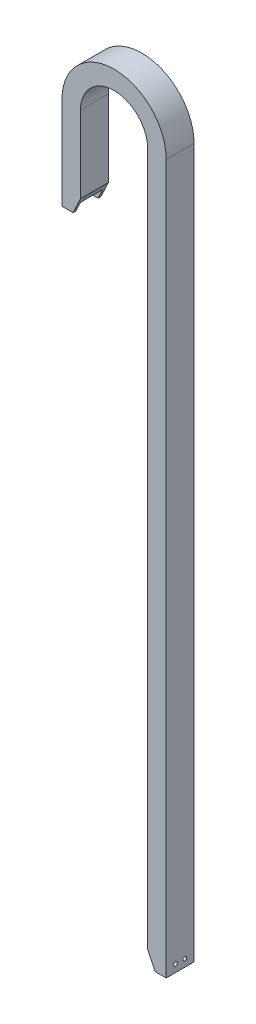
SolidWorks part; units mm, degrees
ref_plane "前视基准面" through (0, 0, 0) normal (0, 0, 1) x (1, 0, 0)
ref_plane "上视基准面" through (0, 0, 0) normal (0, 1, 0) x (1, 0, 0)
ref_plane "右视基准面" through (0, 0, 0) normal (1, 0, 0) x (0, 0, -1)
sketch "草图1" plane through (0, 0, 0) normal (0, 0, 1) x (1, 0, 0)
  line L0 (0, 0) -> (0, 100)
  line L1 (112.5, 100) -> (112.5, -665)
  line L2 (20, 0) -> (20, 100)
  line L3 (92.5, 100) -> (92.5, -665)
  line L4 (0, 0) -> (20, 0)
  line L5 (92.5, -665) -> (112.5, -665)
  arc A0 (0, 100) -> (112.5, 100) centre (56.25, 100) cw
  arc A1 (20, 100) -> (92.5, 100) centre (56.25, 100) cw
  dimension "D1" = 100
  dimension "D3" = 112.5
  dimension "D4" = 765
  dimension "D2" = 20
extrude "凸台-拉伸1" add sketch "草图1" along normal mid plane 30
shell "抽壳1" thickness 3
sketch "草图3" plane through (0, 0, 15) normal (0, 0, 1) x (1, 0, 0)
  line L0 (12, 0) -> (20, 17)
  line L1 (0, 0) -> (20, 0) construction
  line L2 (20, 0) -> (20, 100) construction
  line L3 (20, 17) -> (20, 0)
  line L4 (20, 0) -> (12, 0)
  line L5 (92.5, -665) -> (92.5, -648)
  line L6 (92.5, 100) -> (92.5, -665) construction
  line L7 (92.5, -648) -> (100.5, -665)
  line L9 (100.5, -665) -> (92.5, -665)
  line L10 (92.5, -665) -> (112.5, -665) construction
  line L11 (112.5, -665) -> (112.5, 100) construction
  dimension "D1" = 12
  dimension "D2" = 17
extrude "切除-拉伸1" cut sketch "草图3" against normal through all
sketch "草图4" plane through (109.5, 0, 0) normal (-1, 0, 0) x (0, 0, 1)
  line L0 (0, -665) -> (0, -41.0561) construction
  line L1 (12, -665) -> (-12, -665) construction
  circle A0 centre (-5, -657) radius 2.1
  circle A1 centre (5, -657) radius 2.1
  dimension "D3" = 4.2
  dimension "D1" = 10
  dimension "D2" = 8
extrude "切除-拉伸2" cut sketch "草图4" against normal through all
sketch "草图5" plane through (0, 0, 0) normal (-1, 0, 0) x (0, 0, 1)
  line L0 (0, 0) -> (0, 24.6059) construction
  line L1 (15, 0) -> (-15, 0) construction
  circle A0 centre (-5, 8) radius 2.1
  circle A1 centre (5, 8) radius 2.1
  dimension "D3" = 4.2
  dimension "D1" = 10
  dimension "D2" = 8
extrude "切除-拉伸3" cut sketch "草图5" against normal up to surface (3 mm away) up to face at (3, 50, 0)
